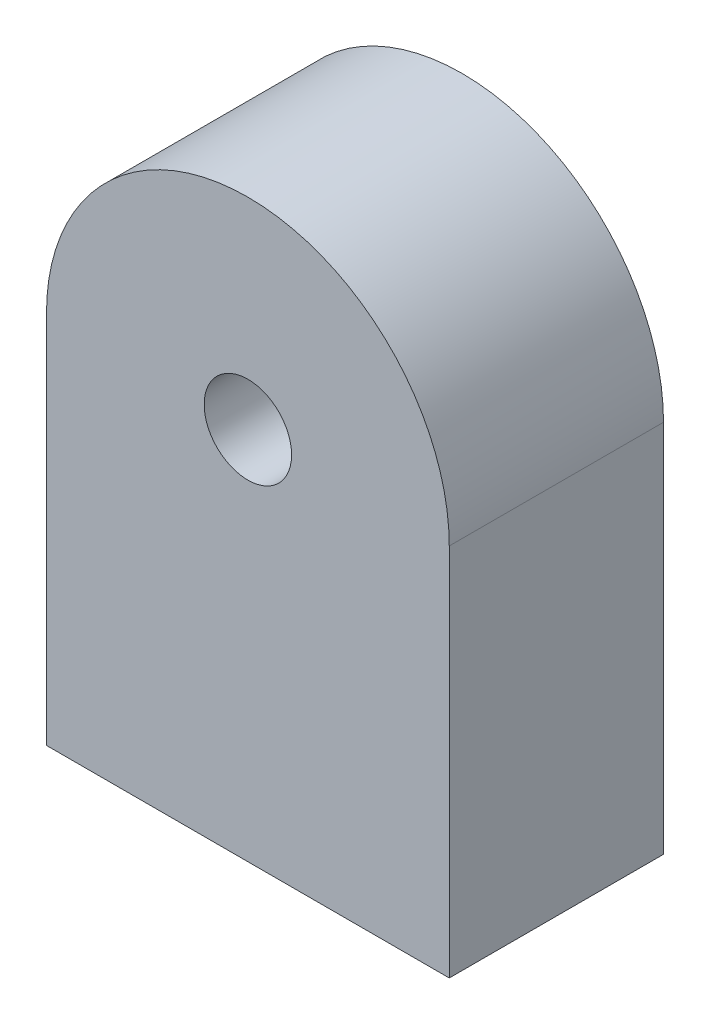
SolidWorks part; units mm, degrees
ref_plane "Plan de face" through (0, 0, 0) normal (0, 0, 1) x (1, 0, 0)
ref_plane "Plan de dessus" through (0, 0, 0) normal (0, 1, 0) x (1, 0, 0)
ref_plane "Plan de droite" through (0, 0, 0) normal (1, 0, 0) x (0, 0, -1)
sketch "Esquisse1" plane through (0, 0, 0) normal (0, 0, 1) x (1, 0, 0)
  line L0 (-6.0337, 0) -> (-6.0337, 4.3662)
  line L1 (-6.0337, 4.3662) -> (-1.3337, 4.3662) construction
  line L2 (-1.3337, 4.3662) -> (-1.3337, 0)
  line L3 (-1.3337, 0) -> (-6.0337, 0)
  arc A0 (-6.0337, 4.3662) -> (-1.3337, 4.3662) centre (-3.6837, 4.3662) cw
  circle A1 centre (-3.6837, 4.3662) radius 0.51
  dimension "D1" = 4.7
extrude "Boss.-Extru.1" add sketch "Esquisse1" along normal blind 2.5
